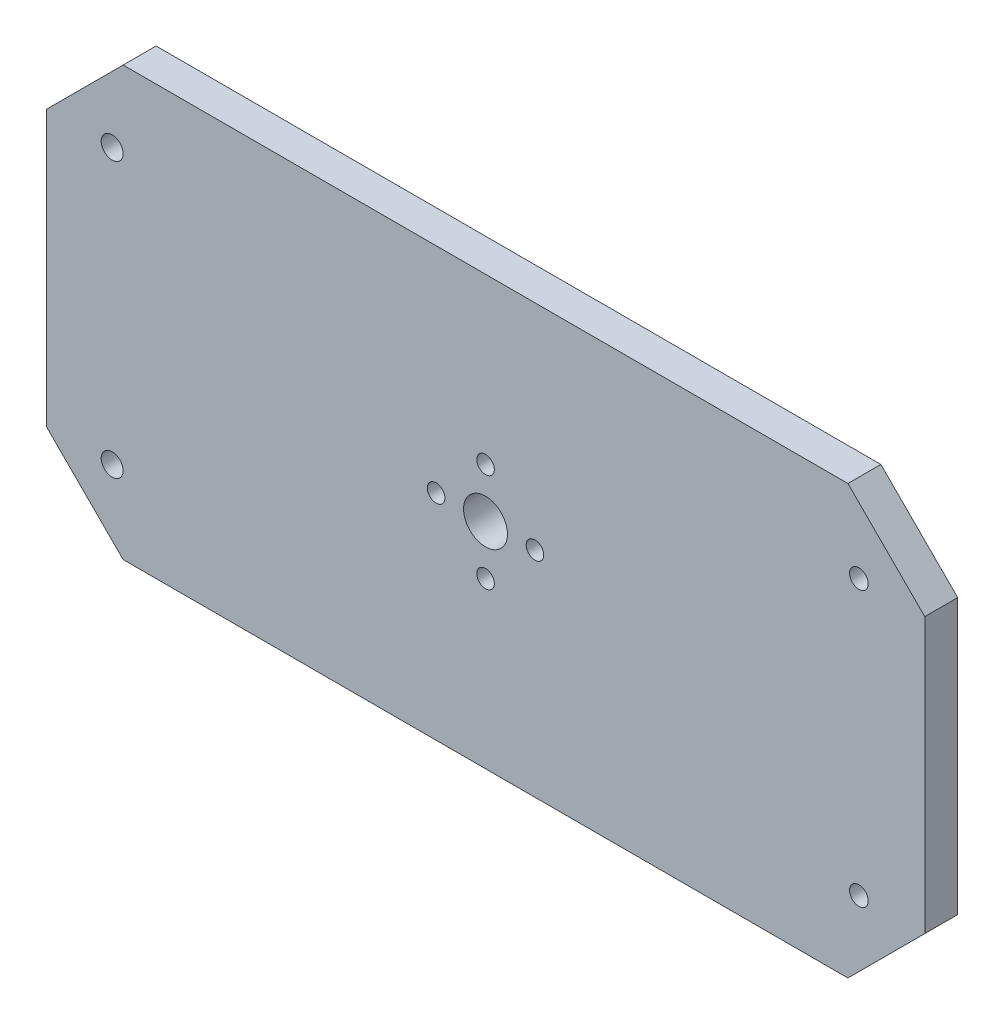
SolidWorks part; units mm, degrees
ref_plane "Спереди" through (0, 0, 0) normal (0, 0, 1) x (1, 0, 0)
ref_plane "Сверху" through (0, 0, 0) normal (0, 1, 0) x (1, 0, 0)
ref_plane "Справа" through (0, 0, 0) normal (1, 0, 0) x (0, 0, -1)
other "Configuration Table"
sketch "Эскиз1" plane through (0, 0, 0) normal (0, 0, 1) x (1, 0, 0)
  line L0 (-66, -39) -> (66, -39)
  line L1 (66, -39) -> (80, -25)
  line L2 (80, -25) -> (80, 25)
  line L3 (80, 25) -> (66, 39)
  line L4 (66, 39) -> (-66, 39)
  line L5 (-66, 39) -> (-80, 25)
  line L6 (-80, 25) -> (-80, -25)
  line L7 (-80, -25) -> (-66, -39)
  circle A0 centre (0, 0) radius 4
  circle A1 centre (-9, 0) radius 1.6
  circle A2 centre (9, 0) radius 1.6
  circle A3 centre (0, 9) radius 1.6
  circle A4 centre (0, -9) radius 1.6
  circle A5 centre (-68, -25) radius 2
  circle A6 centre (-68, 25) radius 2
  circle A7 centre (68, -25) radius 1.7
  circle A8 centre (68, 25) radius 1.7
extrude "06_Rotating_yoke" add sketch "Эскиз1" along normal blind 6
